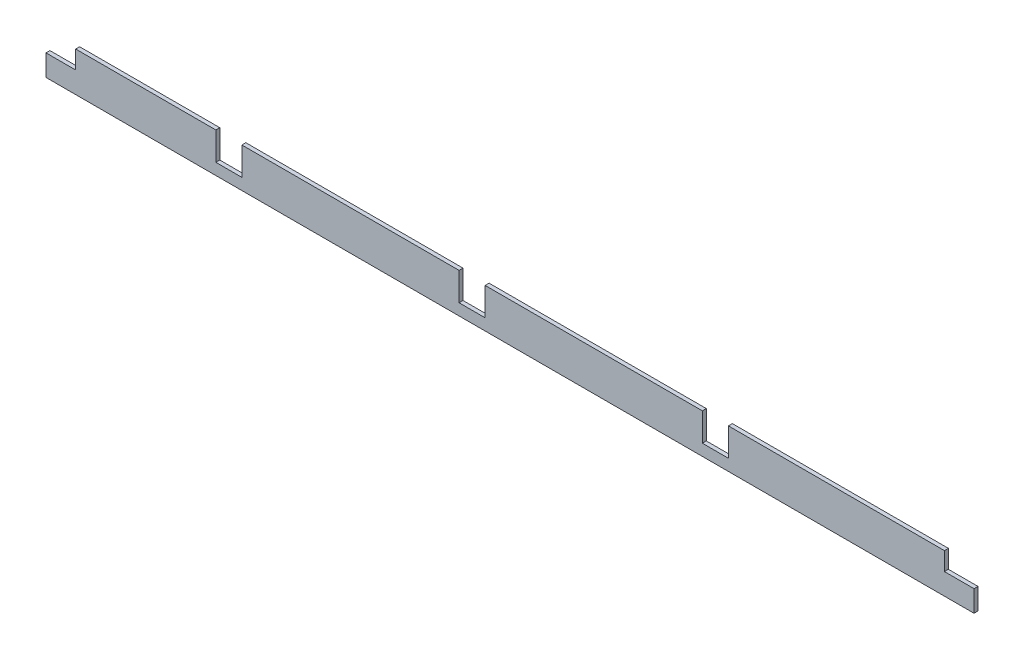
SolidWorks part; units mm, degrees
material "Free-Cutting Brass, UNS C36000"
ref_plane "Front Plane" through (0, 0, 0) normal (0, 0, 1) x (1, 0, 0)
ref_plane "Top Plane" through (0, 0, 0) normal (0, 1, 0) x (1, 0, 0)
ref_plane "Right Plane" through (0, 0, 0) normal (1, 0, 0) x (0, 0, -1)
sketch "Sketch1" plane through (0, 0, 0) normal (0, 0, 1) x (1, 0, 0)
  line L0 (62.992, 12.7) -> (132.842, 12.7)
  line L1 (0, 0) -> (298.45, 0)
  line L2 (0, 0) -> (0, 6.858)
  line L3 (9.525, 12.7) -> (54.61, 12.7)
  line L4 (298.45, 0) -> (298.45, 6.858)
  line L5 (141.224, 12.7) -> (211.074, 12.7)
  line L6 (54.61, 12.7) -> (54.61, 3.683)
  line L7 (54.61, 3.683) -> (62.992, 3.683)
  line L8 (62.992, 12.7) -> (62.992, 3.683)
  line L9 (219.456, 12.7) -> (288.925, 12.7)
  line L10 (132.842, 12.7) -> (132.842, 3.683)
  line L11 (132.842, 3.683) -> (141.224, 3.683)
  line L12 (141.224, 12.7) -> (141.224, 3.683)
  line L14 (211.074, 12.7) -> (211.074, 3.683)
  line L15 (211.074, 3.683) -> (219.456, 3.683)
  line L16 (219.456, 12.7) -> (219.456, 3.683)
  line L17 (298.45, 6.858) -> (288.925, 6.858)
  line L20 (288.925, 6.858) -> (288.925, 12.7)
  line L21 (0, 6.858) -> (9.525, 6.858)
  line L22 (9.525, 12.7) -> (9.525, 6.858)
  dimension "D1" = 298.45
  dimension "D2" = 54.61
  dimension "D3" = 69.85
  dimension "D4" = 69.85
  dimension "D5" = 8.382
  dimension "D6" = 8.382
  dimension "D7" = 8.382
  dimension "D8" = 9.525
  dimension "D9" = 9.017
  dimension "D10" = 12.7
  dimension "D11" = 9.525
  dimension "D12" = 5.842
extrude "Boss-Extrude1" add sketch "Sketch1" along normal blind 1.27
